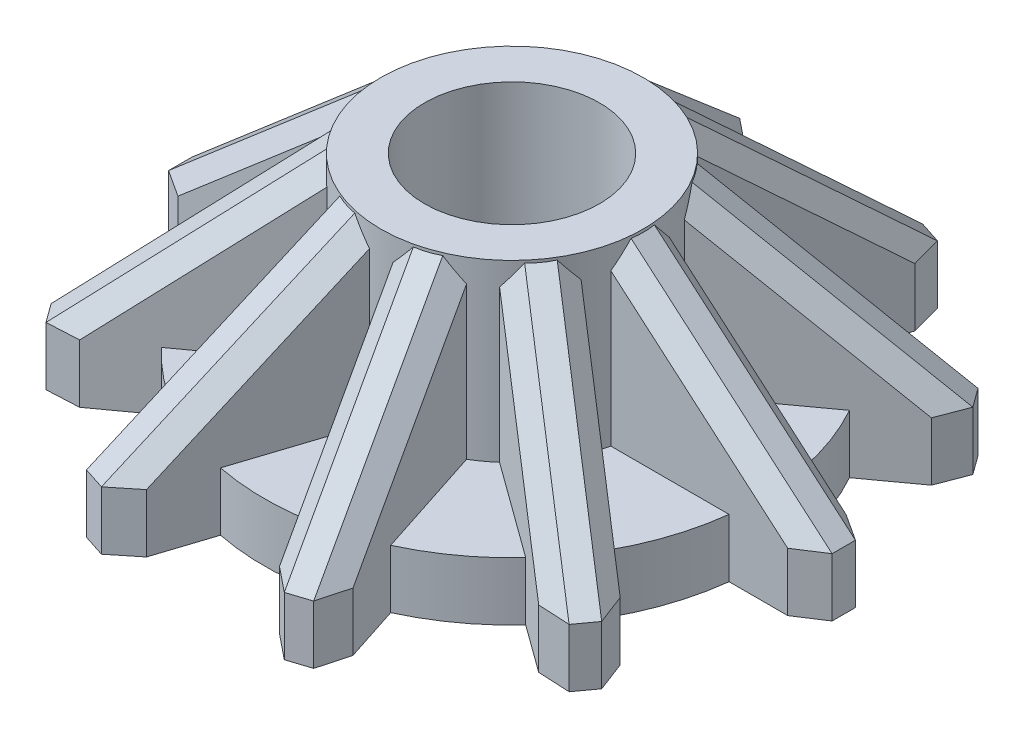
SolidWorks part; units mm, degrees
material "Cast Alloy Steel"
ref_plane "Front" through (0, 0, 0) normal (0, 0, 1) x (1, 0, 0)
ref_plane "Top" through (0, 0, 0) normal (0, 1, 0) x (1, 0, 0)
ref_plane "Right" through (0, 0, 0) normal (1, 0, 0) x (0, 0, -1)
sketch "Sketch1" plane through (0, 0, 0) normal (0, 1, 0) x (1, 0, 0)
  circle A0 centre (0, 0) radius 5.75
  dimension "D1" = 11.5
extrude "Boss-Extrude1" add sketch "Sketch1" along normal blind 1
sketch "Sketch2" plane through (0, 1, 0) normal (0, 1, 0) x (1, 0, 0)
  circle A0 centre (0, 0) radius 2.25
  dimension "D1" = 4.5
extrude "Boss-Extrude2" add sketch "Sketch2" along normal blind 3
sketch "Sketch3" plane through (0, 0, 0) normal (0, 0, 1) x (1, 0, 0)
  line L0 (-2.25, 3.9503) -> (-5.6872, 1)
  line L1 (-2.25, 4) -> (-2.25, 1) construction
  line L2 (5.75, 1) -> (-5.75, 1) construction
rib "Rib2" sketch "Sketch3" sketch "Sketch3" thickness 1 extrusion direction parallel to sketch draft on no parameters "D1"=1
chamfer "Chamfer1" distance 0.3 angle 45 2 edges at (-3.9404, 2.4993, -0.5) (-3.9404, 2.4993, 0.5)
pattern_circular "CirPattern1" count 10 over 360 about axis through (0, 0, 0) along (0, 1, 0) of "Rib2", "Chamfer1"
sketch "Sketch5" plane through (0, 0, 0) normal (0, -1, 0) x (1, 0, 0)
  circle A0 centre (0, 0) radius 2.5
  dimension "D1" = 5
extrude "Boss-Extrude4" add sketch "Sketch5" along normal blind 0.5
sketch "Sketch6" plane through (0, 4, 0) normal (0, 1, 0) x (1, 0, 0)
  circle A0 centre (0, 0) radius 1.5
  dimension "D1" = 3
extrude "Cut-Extrude1" cut sketch "Sketch6" against normal through all
sketch "Sketch8" plane through (0, 1, 0) normal (0, 1, 0) x (1, 0, 0)
  line L0 (-1.9476, -5.347) -> (-1.5672, -5.4706)
  line L1 (-1.5672, -5.4706) -> (-1.1396, -5.1253)
  line L2 (-1.1396, -5.1253) -> (-0.8287, -4.1684)
  line L3 (-1.1396, -5.1253) -> (-0.2024, -2.2409) construction
  line L4 (1.5672, -5.4706) -> (1.1396, -5.1253)
  line L5 (1.1396, -5.1253) -> (0.8287, -4.1684)
  line L6 (1.1396, -5.1253) -> (0.2024, -2.2409) construction
  line L7 (-1.9476, -5.347) -> (-2.389, -6.3222)
  line L8 (-2.389, -6.3222) -> (0.684, -7.7129)
  line L9 (0.684, -7.7129) -> (1.6497, -5.5789)
  line L10 (1.6497, -5.5789) -> (1.5672, -5.4706)
  arc A0 (-0.8287, -4.1684) -> (0.8287, -4.1684) centre (0, 0) ccw
  dimension "D1" = 4.25
extrude "Cut-Extrude2" cut sketch "Sketch8" against normal through all
pattern_circular "CirPattern2" count 10 over 360 about axis through (0, 0, 0) along (0, 1, 0) of "Cut-Extrude2"
